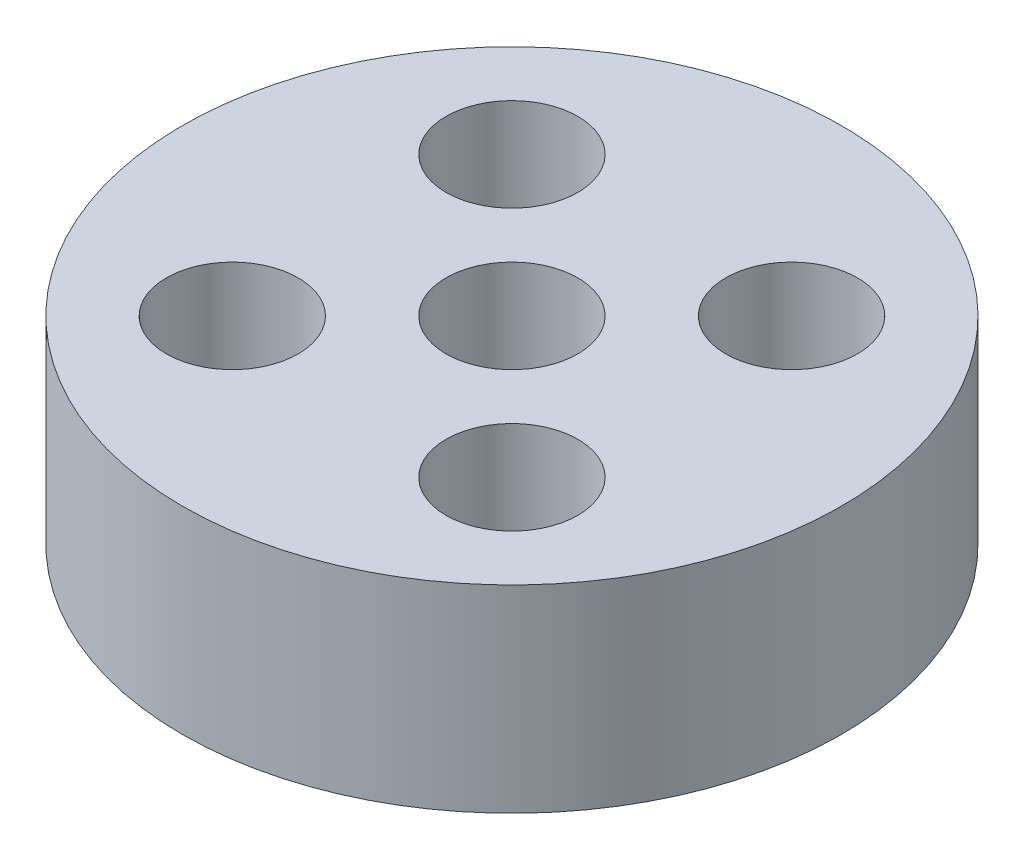
SolidWorks part; units mm, degrees
ref_plane "Front Plane" through (0, 0, 0) normal (0, 0, 1) x (1, 0, 0)
ref_plane "Top Plane" through (0, 0, 0) normal (0, 1, 0) x (1, 0, 0)
ref_plane "Right Plane" through (0, 0, 0) normal (1, 0, 0) x (0, 0, -1)
sketch "Sketch1" plane through (0, 0, 0) normal (0, 1, 0) x (1, 0, 0)
  line L0 (38.9645, 0) -> (-41.374, 0) construction
  line L1 (0, 35.6517) -> (0, -41.5829) construction
  line L2 (0, 0) -> (35.2387, 35.2387) construction
  circle A0 centre (0, 0) radius 25
  circle A1 centre (0, 0) radius 15 construction
  circle A2 centre (10.6066, 10.6066) radius 5
  circle A3 centre (10.6066, -10.6066) radius 5
  circle A4 centre (-10.6066, -10.6066) radius 5
  circle A5 centre (-10.6066, 10.6066) radius 5
  point P20 (0, 0)
  dimension "D1" = 50
  dimension "D2" = 30
  dimension "D3" = 10
  dimension "D4" = 45
  dimension "D5" = 4
extrude "Boss-Extrude1" add sketch "Sketch1" along normal blind 15
sketch "Sketch2" plane through (0, 15, 0) normal (0, 1, 0) x (1, 0, 0)
  circle A0 centre (0, 0) radius 5
  dimension "D1" = 10
extrude "Cut-Extrude1" cut sketch "Sketch2" against normal through all
